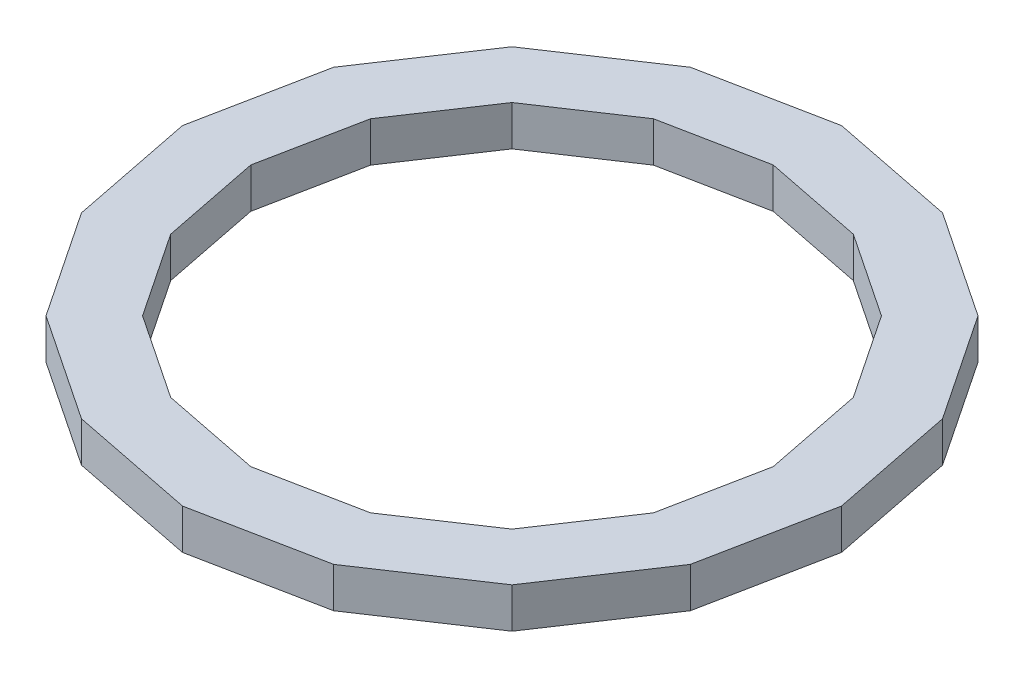
SolidWorks part; units mm, degrees
ref_plane "Front Plane" through (0, 0, 0) normal (0, 0, 1) x (1, 0, 0)
ref_plane "Top Plane" through (0, 0, 0) normal (0, 1, 0) x (1, 0, 0)
ref_plane "Right Plane" through (0, 0, 0) normal (1, 0, 0) x (0, 0, -1)
sketch "Sketch1" plane through (0, 0, 0) normal (0, 1, 0) x (1, 0, 0)
  line L1 (156.2353, 0) -> (144.3426, 59.7887)
  line L2 (144.3426, 59.7887) -> (110.4751, 110.4751)
  line L3 (110.4751, 110.4751) -> (59.7887, 144.3426)
  line L4 (59.7887, 144.3426) -> (0, 156.2353)
  line L5 (0, 156.2353) -> (-59.7887, 144.3426)
  line L6 (-59.7887, 144.3426) -> (-110.4751, 110.4751)
  line L7 (-110.4751, 110.4751) -> (-144.3426, 59.7887)
  line L8 (-144.3426, 59.7887) -> (-156.2353, 0)
  line L9 (-156.2353, 0) -> (-144.3426, -59.7887)
  line L10 (-144.3426, -59.7887) -> (-110.4751, -110.4751)
  line L11 (-110.4751, -110.4751) -> (-59.7887, -144.3426)
  line L12 (-59.7887, -144.3426) -> (0, -156.2353)
  line L13 (0, -156.2353) -> (59.7887, -144.3426)
  line L14 (59.7887, -144.3426) -> (110.4751, -110.4751)
  line L15 (110.4751, -110.4751) -> (144.3426, -59.7887)
  line L16 (144.3426, -59.7887) -> (156.2353, 0)
  line L17 (123.8633, 0) -> (114.4348, 47.4004)
  line L18 (114.4348, 47.4004) -> (87.5846, 87.5846)
  line L19 (87.5846, 87.5846) -> (47.4004, 114.4348)
  line L20 (47.4004, 114.4348) -> (0, 123.8633)
  line L21 (0, 123.8633) -> (-47.4004, 114.4348)
  line L22 (-47.4004, 114.4348) -> (-87.5846, 87.5846)
  line L23 (-87.5846, 87.5846) -> (-114.4348, 47.4004)
  line L24 (-114.4348, 47.4004) -> (-123.8633, 0)
  line L25 (-123.8633, 0) -> (-114.4348, -47.4004)
  line L26 (-114.4348, -47.4004) -> (-87.5846, -87.5846)
  line L27 (-87.5846, -87.5846) -> (-47.4004, -114.4348)
  line L28 (-47.4004, -114.4348) -> (0, -123.8633)
  line L29 (0, -123.8633) -> (47.4004, -114.4348)
  line L30 (47.4004, -114.4348) -> (87.5846, -87.5846)
  line L31 (87.5846, -87.5846) -> (114.4348, -47.4004)
  line L32 (114.4348, -47.4004) -> (123.8633, 0)
  circle A0 centre (0, 0) radius 153.2333 construction
  circle A1 centre (0, 0) radius 121.4833 construction
  dimension "D1" = 31.75
  dimension "D2" = 60.96
extrude "Boss-Extrude1" add sketch "Sketch1" along normal blind 19.05
